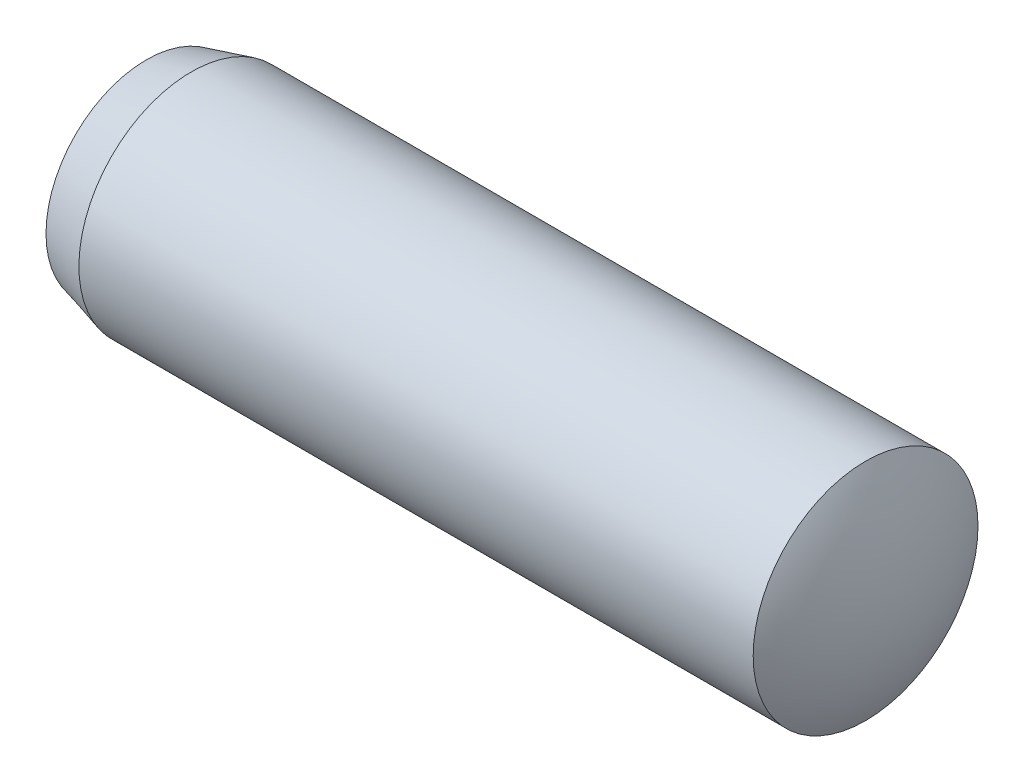
SolidWorks part; units mm, degrees
ref_plane "Přední rovina" through (0, 0, 0) normal (0, 0, 1) x (1, 0, 0)
ref_plane "Vrchní rovina" through (0, 0, 0) normal (0, 1, 0) x (1, 0, 0)
ref_plane "Pravá rovina" through (0, 0, 0) normal (1, 0, 0) x (0, 0, -1)
sketch "Skica1" plane through (0, 0, 0) normal (0, 0, 1) x (1, 0, 0)
  line L0 (0, 0) -> (0, 0.2678)
  line L1 (0, 0.2678) -> (0.12, 0.3)
  line L2 (0.12, 0.3) -> (1.9196, 0.3)
  line L3 (0, 0) -> (1.9196, 0) construction
  line L4 (1.9196, 0) -> (1.9196, 0.3) construction
  line L5 (0, 0) -> (2, 0)
  arc A0 (1.9196, 0.3) -> (2, 0) centre (1.4, 0) cw
  dimension "D3" = 0.6
  dimension "d" = 0.6
  dimension "D2" = 15
  dimension "c" = 0.12
  dimension "l" = 2
revolve "Otočit kolem osy1" add sketch "Skica1" angle 360 about L5
equation "\"D3@Skica1\" = \"d@Skica1\""
